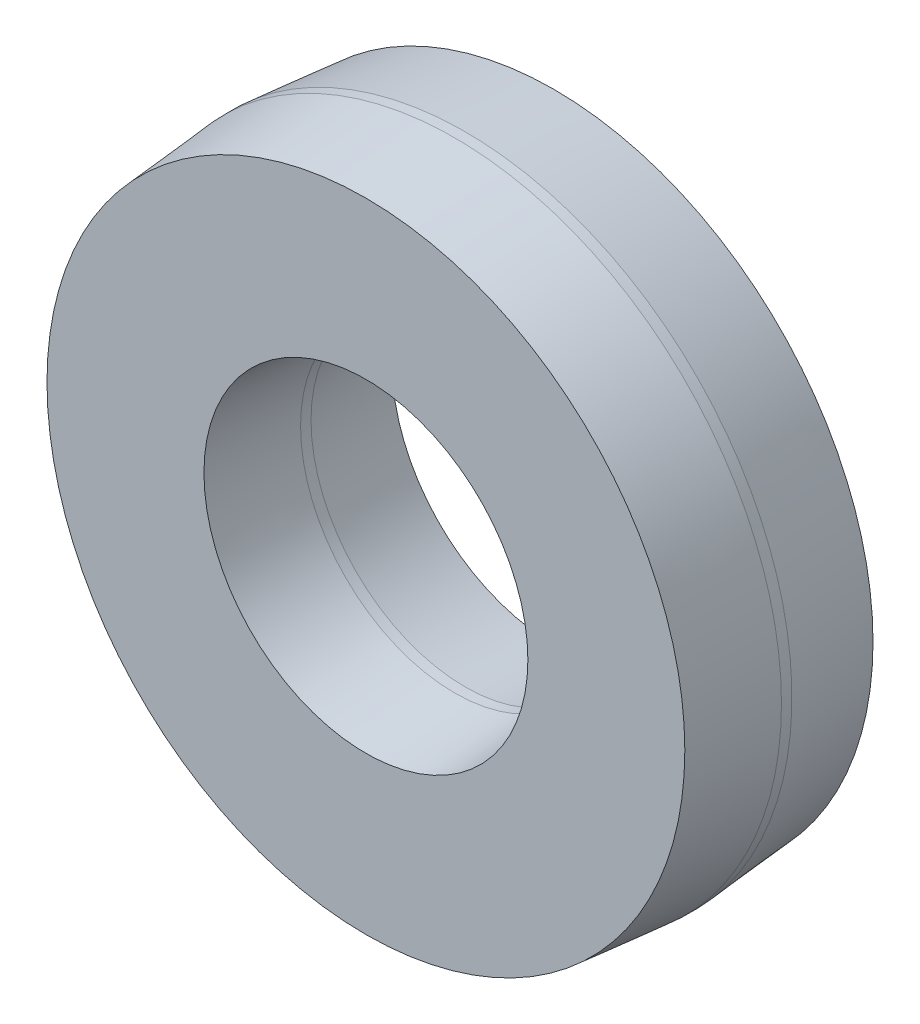
SolidWorks part; units mm, degrees
ref_plane "Спереди" through (0, 0, 0) normal (0, 0, 1) x (1, 0, 0)
ref_plane "Сверху" through (0, 0, 0) normal (0, 1, 0) x (1, 0, 0)
ref_plane "Справа" through (0, 0, 0) normal (1, 0, 0) x (0, 0, -1)
sketch "Эскиз1" plane through (0, 0, 0) normal (0, 0, 1) x (1, 0, 0)
  circle A0 centre (0, 0) radius 62.5
  circle A1 centre (0, 0) radius 29.5
  dimension "D1" = 59
  dimension "D2" = 125
extrude "Вытянуть1" add sketch "Эскиз1" along normal blind 17 draft 5
sketch "Эскиз2" plane through (0, 0, 0) normal (0, 0, -1) x (-1, 0, 0)
  circle A0 centre (0, 0) radius 62.5
  circle A1 centre (0, 0) radius 29.5
  dimension "D1" = 59
  dimension "D2" = 125
extrude "Вытянуть2" add sketch "Эскиз2" along normal blind 2
sketch "Эскиз3" plane through (0, 0, -2) normal (0, 0, -1) x (-1, 0, 0)
  circle A0 centre (0, 0) radius 29.5
  circle A1 centre (0, 0) radius 62.5
  dimension "D1" = 59
  dimension "D2" = 125
extrude "Вытянуть3" add sketch "Эскиз3" along normal blind 17 draft 5
